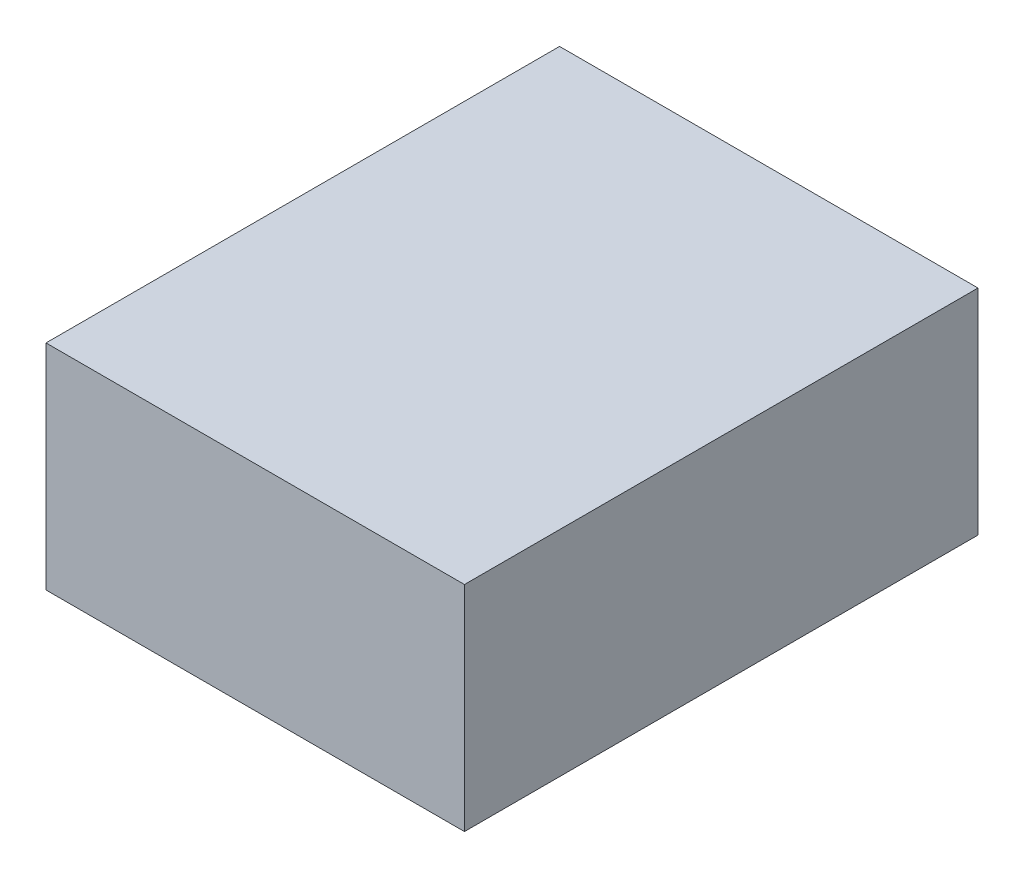
SolidWorks part; units mm, degrees
ref_plane "Front Plane" through (0, 0, 0) normal (0, 0, 1) x (1, 0, 0)
ref_plane "Top Plane" through (0, 0, 0) normal (0, 1, 0) x (1, 0, 0)
ref_plane "Right Plane" through (0, 0, 0) normal (1, 0, 0) x (0, 0, -1)
sketch "Sketch1" plane through (0, 0, 0) normal (1, 0, 0) x (0, 0, -1)
  line L1 (-216, -90) -> (216, -90)
  line L2 (-216, -90) -> (-216, 90)
  line L3 (-216, 90) -> (216, 90)
  line L4 (216, -90) -> (216, 90)
  line L5 (-216, -90) -> (216, 90) construction
  line L6 (-216, 90) -> (216, -90) construction
  point P0 (0, 0)
  dimension "D1" = 432
  dimension "D2" = 180
extrude "Boss-Extrude1" add sketch "Sketch1" along normal blind 352
